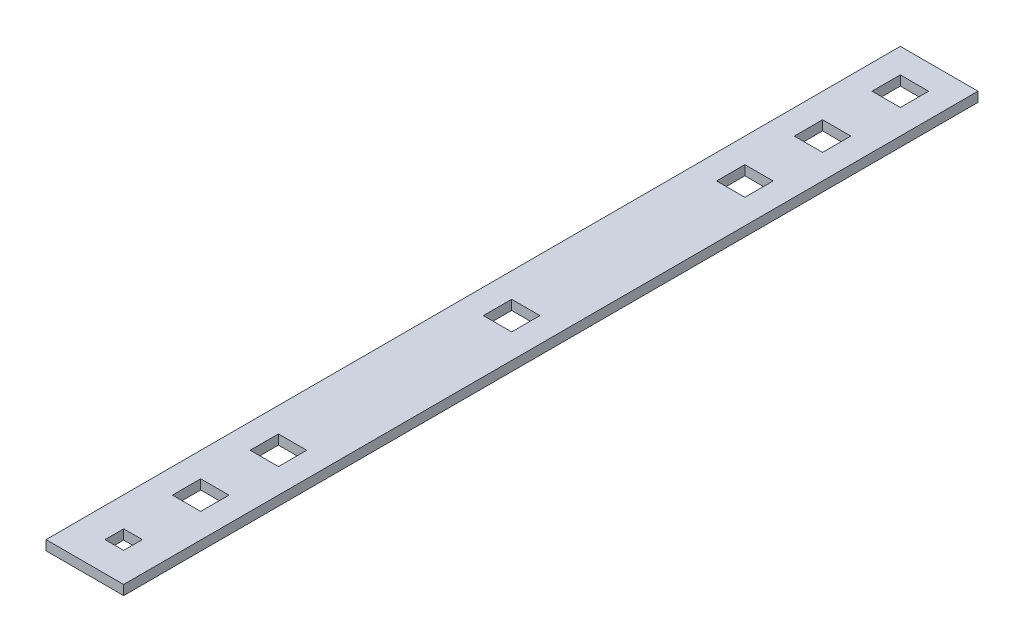
SolidWorks part; units mm, degrees
ref_plane "Front Plane" through (0, 0, 0) normal (0, 0, 1) x (1, 0, 0)
ref_plane "Top Plane" through (0, 0, 0) normal (0, 1, 0) x (1, 0, 0)
ref_plane "Right Plane" through (0, 0, 0) normal (1, 0, 0) x (0, 0, -1)
sketch "Sketch1" plane through (0, 0, 0) normal (0, 1, 0) x (1, 0, 0)
  line L1 (-0.0371, 101.5375) -> (12.6629, 101.5375)
  line L2 (-0.0371, 101.5375) -> (-0.0371, -38.1625)
  line L3 (-0.0371, -38.1625) -> (12.6629, -38.1625)
  line L4 (12.6629, 101.5375) -> (12.6629, -38.1625)
  line L5 (4.0001, 97.4975) -> (8.6229, 97.4975)
  line L6 (4.0001, 97.4975) -> (4.0001, 92.8747)
  line L7 (4.0001, 92.8747) -> (8.6229, 92.8747)
  line L8 (8.6229, 97.4975) -> (8.6229, 92.8747)
  line L40 (4.0001, 84.7863) -> (4.0001, 80.1635)
  line L41 (4.0001, 84.7863) -> (8.6229, 84.7863)
  line L42 (8.6229, 84.7863) -> (8.6229, 80.1635)
  line L43 (4.0001, 80.1635) -> (8.6229, 80.1635)
  line L44 (4.0001, 72.075) -> (4.0001, 67.4522)
  line L45 (4.0001, 72.075) -> (8.6229, 72.075)
  line L46 (8.6229, 72.075) -> (8.6229, 67.4522)
  line L47 (4.0001, 67.4522) -> (8.6229, 67.4522)
  line L49 (4.7899, -30.2895) -> (7.8379, -30.2895)
  line L50 (4.7899, -30.2895) -> (4.7899, -33.3375)
  line L51 (4.7899, -33.3375) -> (7.8379, -33.3375)
  line L52 (7.8379, -30.2895) -> (7.8379, -33.3375)
  line L60 (4.0001, 33.9411) -> (4.0001, 29.3183)
  line L61 (4.0001, 33.9411) -> (8.6229, 33.9411)
  line L62 (8.6229, 33.9411) -> (8.6229, 29.3183)
  line L63 (4.0001, 29.3183) -> (8.6229, 29.3183)
  line L72 (4.0001, -4.1927) -> (4.0001, -8.8155)
  line L73 (4.0001, -4.1927) -> (8.6229, -4.1927)
  line L74 (8.6229, -4.1927) -> (8.6229, -8.8155)
  line L75 (4.0001, -8.8155) -> (8.6229, -8.8155)
  line L76 (4.0001, -16.904) -> (4.0001, -21.5268)
  line L77 (4.0001, -16.904) -> (8.6229, -16.904)
  line L78 (8.6229, -16.904) -> (8.6229, -21.5268)
  line L79 (4.0001, -21.5268) -> (8.6229, -21.5268)
  line L80 (4.0001, 46.6524) -> (4.0001, 42.0296) [skipped]
  line L81 (4.0001, 42.0296) -> (8.6229, 42.0296) [skipped]
  line L82 (8.6229, 46.6524) -> (8.6229, 42.0296) [skipped]
  line L83 (4.0001, 46.6524) -> (8.6229, 46.6524) [skipped]
  line L84 (4.0001, 59.3637) -> (4.0001, 54.7409) [skipped]
  line L85 (4.0001, 54.7409) -> (8.6229, 54.7409) [skipped]
  line L86 (8.6229, 59.3637) -> (8.6229, 54.7409) [skipped]
  line L87 (4.0001, 59.3637) -> (8.6229, 59.3637) [skipped]
  line L88 (4.0001, 21.2299) -> (4.0001, 16.6071) [skipped]
  line L89 (4.0001, 16.6071) -> (8.6229, 16.6071) [skipped]
  line L90 (8.6229, 21.2299) -> (8.6229, 16.6071) [skipped]
  line L91 (4.0001, 21.2299) -> (8.6229, 21.2299) [skipped]
  line L92 (4.0001, 8.5186) -> (4.0001, 3.8958) [skipped]
  line L93 (4.0001, 3.8958) -> (8.6229, 3.8958) [skipped]
  line L94 (8.6229, 8.5186) -> (8.6229, 3.8958) [skipped]
  line L95 (4.0001, 8.5186) -> (8.6229, 8.5186) [skipped]
  point P8 (6.3129, 101.5375)
  dimension "D1" = 12.7
  dimension "D2" = 139.7
  dimension "D3" = 4.6228
  dimension "D4" = 4.6228
  dimension "D5" = 4.04
  dimension "D6" = 4.04
  dimension "D8" = 3.048
  dimension "D9" = 3.048
  dimension "D10" = 4.825
  dimension "D11" = 4.825
  dimension "D7" = 10
extrude "Boss-Extrude1" add sketch "Sketch1" along normal blind 1.5875
